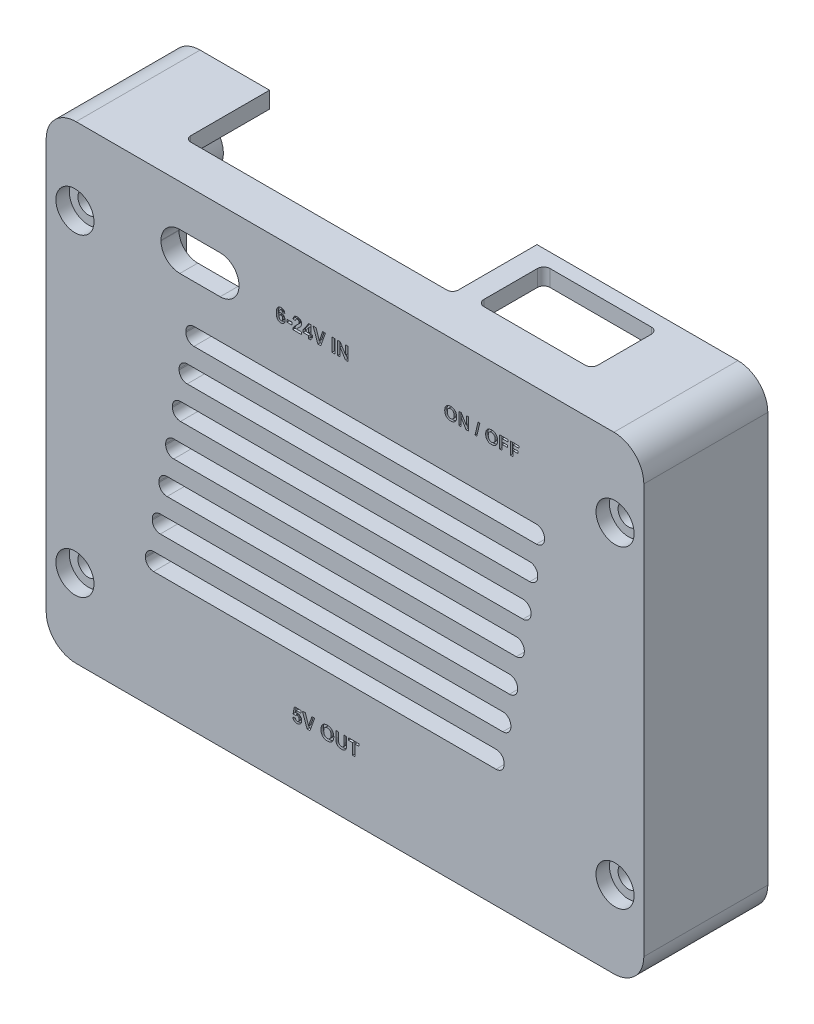
SolidWorks part; units mm, degrees
ref_plane "前视基准面" through (0, 0, 0) normal (0, 0, 1) x (1, 0, 0)
ref_plane "上视基准面" through (0, 0, 0) normal (0, 1, 0) x (1, 0, 0)
ref_plane "右视基准面" through (0, 0, 0) normal (1, 0, 0) x (0, 0, -1)
other "Configuration Table"
sketch "Lid_Envelope_80x62p8_R4" plane through (0, 0, 0) normal (0, 0, 1) x (1, 0, 0)
  line L0 (-36, -31.4) -> (36, -31.4)
  line L1 (40, -27.4) -> (40, 27.4)
  line L2 (36, 31.4) -> (-36, 31.4)
  line L3 (-40, 27.4) -> (-40, -27.4)
  arc A0 (36, -31.4) -> (40, -27.4) centre (36, -27.4) ccw
  arc A1 (40, 27.4) -> (36, 31.4) centre (36, 27.4) ccw
  arc A2 (-36, 31.4) -> (-40, 27.4) centre (-36, 27.4) ccw
  arc A3 (-40, -27.4) -> (-36, -31.4) centre (-36, -27.4) ccw
extrude "Upper_Case_Blank" add sketch "Lid_Envelope_80x62p8_R4" along normal blind 16.6 from offset 8
sketch "Upper_Case_Cavity_2p2_Wall_Profile" plane through (0, 0, 0) normal (0, 0, 1) x (1, 0, 0)
  line L0 (-36, -29.2) -> (36, -29.2)
  line L1 (37.8, -27.4) -> (37.8, 27.4)
  line L2 (36, 29.2) -> (-36, 29.2)
  line L3 (-37.8, 27.4) -> (-37.8, -27.4)
  arc A0 (36, -29.2) -> (37.8, -27.4) centre (36, -27.4) ccw
  arc A1 (37.8, 27.4) -> (36, 29.2) centre (36, 27.4) ccw
  arc A2 (-36, 29.2) -> (-37.8, 27.4) centre (-36, 27.4) ccw
  arc A3 (-37.8, -27.4) -> (-36, -29.2) centre (-36, -27.4) ccw
extrude "Upper_Case_Cavity_2p2_Wall" cut sketch "Upper_Case_Cavity_2p2_Wall_Profile" along normal blind 14.7 from offset 7.5
sketch "Upper_Lid_Screw_Guides_Profile" plane through (0, 0, 0) normal (0, 0, 1) x (1, 0, 0)
  circle A0 centre (-36.15, -21) radius 3.27
  circle A1 centre (-36.15, 21) radius 3.27
  circle A2 centre (36.15, -21) radius 3.27
  circle A3 centre (36.15, 21) radius 3.27
extrude "Upper_Lid_Screw_Guides" add sketch "Upper_Lid_Screw_Guides_Profile" along normal blind 14.3 from offset 8
sketch "Lid_M2p5_Clearance_Profiles" plane through (0, 0, 0) normal (0, 0, 1) x (1, 0, 0)
  circle A0 centre (-36.15, -21) radius 1.4
  circle A1 centre (-36.15, 21) radius 1.4
  circle A2 centre (36.15, -21) radius 1.4
  circle A3 centre (36.15, 21) radius 1.4
extrude "Four_M2p5_Lid_Clearance_Holes_D2p8" cut sketch "Lid_M2p5_Clearance_Profiles" along normal blind 17.6 from offset 7.5
sketch "Lid_Screw_Head_Recess_Profiles" plane through (0, 0, 0) normal (0, 0, 1) x (1, 0, 0)
  circle A0 centre (-36.15, -21) radius 2.55
  circle A1 centre (-36.15, 21) radius 2.55
  circle A2 centre (36.15, -21) radius 2.55
  circle A3 centre (36.15, 21) radius 2.55
extrude "Four_D5p1_Head_Counterbores" cut sketch "Lid_Screw_Head_Recess_Profiles" along normal blind 2.2 from offset 22.8
sketch "Seven_Roof_Vent_Profiles" plane through (0, 0, 0) normal (0, 0, 1) x (1, 0, 0)
  line L0 (-25.62, -15.56) -> (20.22, -15.56)
  line L1 (21.3, -14.48) -> (21.3, -14.32)
  line L2 (20.22, -13.24) -> (-25.62, -13.24)
  line L3 (-26.7, -14.32) -> (-26.7, -14.48)
  line L4 (-24.72, -10.76) -> (21.12, -10.76)
  line L5 (22.2, -9.68) -> (22.2, -9.52)
  line L6 (21.12, -8.44) -> (-24.72, -8.44)
  line L7 (-25.8, -9.52) -> (-25.8, -9.68)
  line L8 (-23.82, -5.96) -> (22.02, -5.96)
  line L9 (23.1, -4.88) -> (23.1, -4.72)
  line L10 (22.02, -3.64) -> (-23.82, -3.64)
  line L11 (-24.9, -4.72) -> (-24.9, -4.88)
  line L12 (-22.92, -1.16) -> (22.92, -1.16)
  line L13 (24, -0.08) -> (24, 0.08)
  line L14 (22.92, 1.16) -> (-22.92, 1.16)
  line L15 (-24, 0.08) -> (-24, -0.08)
  line L16 (-22.02, 3.64) -> (23.82, 3.64)
  line L17 (24.9, 4.72) -> (24.9, 4.88)
  line L18 (23.82, 5.96) -> (-22.02, 5.96)
  line L19 (-23.1, 4.88) -> (-23.1, 4.72)
  line L20 (-21.12, 8.44) -> (24.72, 8.44)
  line L21 (25.8, 9.52) -> (25.8, 9.68)
  line L22 (24.72, 10.76) -> (-21.12, 10.76)
  line L23 (-22.2, 9.68) -> (-22.2, 9.52)
  line L24 (-20.22, 13.24) -> (25.62, 13.24)
  line L25 (26.7, 14.32) -> (26.7, 14.48)
  line L26 (25.62, 15.56) -> (-20.22, 15.56)
  line L27 (-21.3, 14.48) -> (-21.3, 14.32)
  arc A0 (20.22, -15.56) -> (21.3, -14.48) centre (20.22, -14.48) ccw
  arc A1 (21.3, -14.32) -> (20.22, -13.24) centre (20.22, -14.32) ccw
  arc A2 (-25.62, -13.24) -> (-26.7, -14.32) centre (-25.62, -14.32) ccw
  arc A3 (-26.7, -14.48) -> (-25.62, -15.56) centre (-25.62, -14.48) ccw
  arc A4 (21.12, -10.76) -> (22.2, -9.68) centre (21.12, -9.68) ccw
  arc A5 (22.2, -9.52) -> (21.12, -8.44) centre (21.12, -9.52) ccw
  arc A6 (-24.72, -8.44) -> (-25.8, -9.52) centre (-24.72, -9.52) ccw
  arc A7 (-25.8, -9.68) -> (-24.72, -10.76) centre (-24.72, -9.68) ccw
  arc A8 (22.02, -5.96) -> (23.1, -4.88) centre (22.02, -4.88) ccw
  arc A9 (23.1, -4.72) -> (22.02, -3.64) centre (22.02, -4.72) ccw
  arc A10 (-23.82, -3.64) -> (-24.9, -4.72) centre (-23.82, -4.72) ccw
  arc A11 (-24.9, -4.88) -> (-23.82, -5.96) centre (-23.82, -4.88) ccw
  arc A12 (22.92, -1.16) -> (24, -0.08) centre (22.92, -0.08) ccw
  arc A13 (24, 0.08) -> (22.92, 1.16) centre (22.92, 0.08) ccw
  arc A14 (-22.92, 1.16) -> (-24, 0.08) centre (-22.92, 0.08) ccw
  arc A15 (-24, -0.08) -> (-22.92, -1.16) centre (-22.92, -0.08) ccw
  arc A16 (23.82, 3.64) -> (24.9, 4.72) centre (23.82, 4.72) ccw
  arc A17 (24.9, 4.88) -> (23.82, 5.96) centre (23.82, 4.88) ccw
  arc A18 (-22.02, 5.96) -> (-23.1, 4.88) centre (-22.02, 4.88) ccw
  arc A19 (-23.1, 4.72) -> (-22.02, 3.64) centre (-22.02, 4.72) ccw
  arc A20 (24.72, 8.44) -> (25.8, 9.52) centre (24.72, 9.52) ccw
  arc A21 (25.8, 9.68) -> (24.72, 10.76) centre (24.72, 9.68) ccw
  arc A22 (-21.12, 10.76) -> (-22.2, 9.68) centre (-21.12, 9.68) ccw
  arc A23 (-22.2, 9.52) -> (-21.12, 8.44) centre (-21.12, 9.52) ccw
  arc A24 (25.62, 13.24) -> (26.7, 14.32) centre (25.62, 14.32) ccw
  arc A25 (26.7, 14.48) -> (25.62, 15.56) centre (25.62, 14.48) ccw
  arc A26 (-20.22, 15.56) -> (-21.3, 14.48) centre (-20.22, 14.48) ccw
  arc A27 (-21.3, 14.32) -> (-20.22, 13.24) centre (-20.22, 14.32) ccw
extrude "Roof_Vent_Slots" cut sketch "Seven_Roof_Vent_Profiles" along normal blind 3.05 from offset 21.9
sketch "Terminal_Driver_Access_Profiles" plane through (0, 0, 0) normal (0, 0, 1) x (1, 0, 0)
  circle A0 centre (-21.95, 23.3) radius 2.45
  circle A1 centre (-16.87, 23.3) radius 2.45
extrude "Two_KF301_Driver_Access_D4p9" cut sketch "Terminal_Driver_Access_Profiles" along normal blind 3.05 from offset 21.9
sketch "Output_Windows_USB_C_PH_DC_Header_Profile" plane through (0, 0, 0) normal (0, 1, 0) x (1, 0, 0)
  line L0 (10.62, -15.25) -> (25.6, -15.25)
  line L1 (26.3, -14.55) -> (26.3, -6.85)
  line L2 (25.6, -6.15) -> (10.62, -6.15)
  line L3 (9.92, -6.85) -> (9.92, -14.55)
  line L4 (-28.53, -5.65) -> (7.8, -5.65)
  line L5 (7.8, -5.65) -> (8.45, -6.3)
  line L6 (8.45, -6.3) -> (8.45, -17.9)
  line L7 (8.45, -17.9) -> (7.8, -18.55)
  line L8 (7.8, -18.55) -> (-3.4, -18.55)
  line L9 (-3.4, -18.55) -> (-4.05, -17.9)
  line L10 (-4.05, -17.9) -> (-4.05, -14.03)
  line L11 (-4.05, -14.03) -> (-4.7, -13.38)
  line L12 (-4.7, -13.38) -> (-28.53, -13.38)
  line L13 (-28.53, -13.38) -> (-29.18, -12.73)
  line L14 (-29.18, -12.73) -> (-29.18, -6.3)
  line L15 (-29.18, -6.3) -> (-28.53, -5.65)
  arc A0 (25.6, -15.25) -> (26.3, -14.55) centre (25.6, -14.55) ccw
  arc A1 (26.3, -6.85) -> (25.6, -6.15) centre (25.6, -6.85) ccw
  arc A2 (10.62, -6.15) -> (9.92, -6.85) centre (10.62, -6.85) ccw
  arc A3 (9.92, -14.55) -> (10.62, -15.25) centre (10.62, -14.55) ccw
extrude "Output_Windows_USB_C_PH_DC_Header" cut sketch "Output_Windows_USB_C_PH_DC_Header_Profile" along normal blind 3.9 from offset 32.4
sketch "Input_Windows_KF301_XH_DC_Switch_Profile" plane through (0, 0, 0) normal (0, 1, 0) x (1, 0, 0)
  line L0 (-25.95, -19.3) -> (8.35, -19.3)
  line L1 (9.1, -18.55) -> (9.1, -6.9)
  line L2 (8.35, -6.15) -> (-25.95, -6.15)
  line L3 (-26.7, -6.9) -> (-26.7, -18.55)
  line L4 (12.75, -18.75) -> (26.3, -18.75)
  line L5 (27.15, -17.9) -> (27.15, -10.75)
  line L6 (26.3, -9.9) -> (12.75, -9.9)
  line L7 (11.9, -10.75) -> (11.9, -17.9)
  arc A0 (8.35, -19.3) -> (9.1, -18.55) centre (8.35, -18.55) ccw
  arc A1 (9.1, -6.9) -> (8.35, -6.15) centre (8.35, -6.9) ccw
  arc A2 (-25.95, -6.15) -> (-26.7, -6.9) centre (-25.95, -6.9) ccw
  arc A3 (-26.7, -18.55) -> (-25.95, -19.3) centre (-25.95, -18.55) ccw
  arc A4 (26.3, -18.75) -> (27.15, -17.9) centre (26.3, -17.9) ccw
  arc A5 (27.15, -10.75) -> (26.3, -9.9) centre (26.3, -10.75) ccw
  arc A6 (12.75, -9.9) -> (11.9, -10.75) centre (12.75, -10.75) ccw
  arc A7 (11.9, -17.9) -> (12.75, -18.75) centre (12.75, -17.9) ccw
extrude "Input_Windows_KF301_XH_DC_Switch" cut sketch "Input_Windows_KF301_XH_DC_Switch_Profile" against normal blind 3.9 from offset 32.4
sketch "Input_Label_Letter_Profiles" plane through (0, 0, 0) normal (0, 0, 1) x (1, 0, 0)
  line L0 (-8.0456, 23.1366) -> (-8.374, 23.1003)
  line L1 (-8.374, 23.1003) -> (-8.3957, 23.1885)
  line L2 (-8.3957, 23.1885) -> (-8.4367, 23.2501)
  line L3 (-8.4367, 23.2501) -> (-8.495, 23.2863)
  line L4 (-8.495, 23.2863) -> (-8.5683, 23.2983)
  line L5 (-8.5683, 23.2983) -> (-8.6675, 23.2742)
  line L6 (-8.6675, 23.2742) -> (-8.75, 23.2018)
  line L7 (-8.75, 23.2018) -> (-8.7837, 23.1404)
  line L8 (-8.7837, 23.1404) -> (-8.8106, 23.0529)
  line L9 (-8.8106, 23.0529) -> (-8.8305, 22.9394)
  line L10 (-8.8305, 22.9394) -> (-8.8436, 22.7997)
  line L11 (-8.8436, 22.7997) -> (-8.7523, 22.8829)
  line L12 (-8.7523, 22.8829) -> (-8.6472, 22.9328)
  line L13 (-8.6472, 22.9328) -> (-8.5285, 22.9494)
  line L14 (-8.5285, 22.9494) -> (-8.4261, 22.9393)
  line L15 (-8.4261, 22.9393) -> (-8.3312, 22.909)
  line L16 (-8.3312, 22.909) -> (-8.244, 22.8584)
  line L17 (-8.244, 22.8584) -> (-8.1645, 22.7876)
  line L18 (-8.1645, 22.7876) -> (-8.0982, 22.7008)
  line L19 (-8.0982, 22.7008) -> (-8.0508, 22.6023)
  line L20 (-8.0508, 22.6023) -> (-8.0224, 22.492)
  line L21 (-8.0224, 22.492) -> (-8.013, 22.3699)
  line L22 (-8.013, 22.3699) -> (-8.0193, 22.2655)
  line L23 (-8.0193, 22.2655) -> (-8.0384, 22.1697)
  line L24 (-8.0384, 22.1697) -> (-8.0703, 22.0826)
  line L25 (-8.0703, 22.0826) -> (-8.115, 22.004)
  line L26 (-8.115, 22.004) -> (-8.1723, 21.934)
  line L27 (-8.1723, 21.934) -> (-8.2577, 21.8622)
  line L28 (-8.2577, 21.8622) -> (-8.3543, 21.8109)
  line L29 (-8.3543, 21.8109) -> (-8.4623, 21.7801)
  line L30 (-8.4623, 21.7801) -> (-8.5816, 21.7698)
  line L31 (-8.5816, 21.7698) -> (-8.685, 21.7782)
  line L32 (-8.685, 21.7782) -> (-8.7808, 21.8031)
  line L33 (-8.7808, 21.8031) -> (-8.8689, 21.8448)
  line L34 (-8.8689, 21.8448) -> (-8.9494, 21.9031)
  line L35 (-8.9494, 21.9031) -> (-9.0223, 21.9781)
  line L36 (-9.0223, 21.9781) -> (-9.0845, 22.072)
  line L37 (-9.0845, 22.072) -> (-9.1328, 22.1873)
  line L38 (-9.1328, 22.1873) -> (-9.1673, 22.3239)
  line L39 (-9.1673, 22.3239) -> (-9.1881, 22.4817)
  line L40 (-9.1881, 22.4817) -> (-9.195, 22.6608)
  line L41 (-9.195, 22.6608) -> (-9.1878, 22.8446)
  line L42 (-9.1878, 22.8446) -> (-9.1662, 23.0066)
  line L43 (-9.1662, 23.0066) -> (-9.1302, 23.1469)
  line L44 (-9.1302, 23.1469) -> (-9.0798, 23.2655)
  line L45 (-9.0798, 23.2655) -> (-9.0151, 23.3623)
  line L46 (-9.0151, 23.3623) -> (-8.9388, 23.4397)
  line L47 (-8.9388, 23.4397) -> (-8.8539, 23.4999)
  line L48 (-8.8539, 23.4999) -> (-8.7605, 23.5429)
  line L49 (-8.7605, 23.5429) -> (-8.6585, 23.5687)
  line L50 (-8.6585, 23.5687) -> (-8.5478, 23.5772)
  line L51 (-8.5478, 23.5772) -> (-8.4211, 23.5647)
  line L52 (-8.4211, 23.5647) -> (-8.3098, 23.5271)
  line L53 (-8.3098, 23.5271) -> (-8.214, 23.4644)
  line L54 (-8.214, 23.4644) -> (-8.1539, 23.4015)
  line L55 (-8.1539, 23.4015) -> (-8.1058, 23.326)
  line L56 (-8.1058, 23.326) -> (-8.0697, 23.2376)
  line L57 (-8.0697, 23.2376) -> (-8.0456, 23.1366)
  line L58 (-8.8146, 22.3964) -> (-8.8062, 22.2946)
  line L59 (-8.8062, 22.2946) -> (-8.7808, 22.2094)
  line L60 (-8.7808, 22.2094) -> (-8.7386, 22.1411)
  line L61 (-8.7386, 22.1411) -> (-8.6571, 22.0736)
  line L62 (-8.6571, 22.0736) -> (-8.5647, 22.0511)
  line L63 (-8.5647, 22.0511) -> (-8.4784, 22.0695)
  line L64 (-8.4784, 22.0695) -> (-8.4078, 22.1248)
  line L65 (-8.4078, 22.1248) -> (-8.3607, 22.222)
  line L66 (-8.3607, 22.222) -> (-8.345, 22.3663)
  line L67 (-8.345, 22.3663) -> (-8.3525, 22.4711)
  line L68 (-8.3525, 22.4711) -> (-8.375, 22.5554)
  line L69 (-8.375, 22.5554) -> (-8.4126, 22.6192)
  line L70 (-8.4126, 22.6192) -> (-8.4886, 22.6794)
  line L71 (-8.4886, 22.6794) -> (-8.5816, 22.6995)
  line L72 (-8.5816, 22.6995) -> (-8.6719, 22.6803)
  line L73 (-8.6719, 22.6803) -> (-8.747, 22.6228)
  line L74 (-8.747, 22.6228) -> (-8.7977, 22.5279)
  line L75 (-8.7977, 22.5279) -> (-8.8146, 22.3964)
  line L76 (-7.7642, 22.2721) -> (-7.7642, 22.6114)
  line L77 (-7.7642, 22.6114) -> (-7.0978, 22.6114)
  line L78 (-7.0978, 22.6114) -> (-7.0978, 22.2721)
  line L79 (-7.0978, 22.2721) -> (-7.7642, 22.2721)
  line L80 (-5.8071, 22.1151) -> (-5.8071, 21.8)
  line L81 (-5.8071, 21.8) -> (-6.9963, 21.8)
  line L82 (-6.9963, 21.8) -> (-6.9749, 21.917)
  line L83 (-6.9749, 21.917) -> (-6.9362, 22.0299)
  line L84 (-6.9362, 22.0299) -> (-6.8804, 22.1387)
  line L85 (-6.8804, 22.1387) -> (-6.8343, 22.2068)
  line L86 (-6.8343, 22.2068) -> (-6.773, 22.2834)
  line L87 (-6.773, 22.2834) -> (-6.6967, 22.3682)
  line L88 (-6.6967, 22.3682) -> (-6.6053, 22.4615)
  line L89 (-6.6053, 22.4615) -> (-6.4989, 22.5631)
  line L90 (-6.4989, 22.5631) -> (-6.3953, 22.6613)
  line L91 (-6.3953, 22.6613) -> (-6.3139, 22.7423)
  line L92 (-6.3139, 22.7423) -> (-6.2546, 22.8062)
  line L93 (-6.2546, 22.8062) -> (-6.2176, 22.8528)
  line L94 (-6.2176, 22.8528) -> (-6.1651, 22.9573)
  line L95 (-6.1651, 22.9573) -> (-6.1476, 23.0605)
  line L96 (-6.1476, 23.0605) -> (-6.1628, 23.1608)
  line L97 (-6.1628, 23.1608) -> (-6.2085, 23.235)
  line L98 (-6.2085, 23.235) -> (-6.2811, 23.2807)
  line L99 (-6.2811, 23.2807) -> (-6.377, 23.2959)
  line L100 (-6.377, 23.2959) -> (-6.4723, 23.2799)
  line L101 (-6.4723, 23.2799) -> (-6.546, 23.2319)
  line L102 (-6.546, 23.2319) -> (-6.5955, 23.1468)
  line L103 (-6.5955, 23.1468) -> (-6.6184, 23.0194)
  line L104 (-6.6184, 23.0194) -> (-6.9565, 23.0532)
  line L105 (-6.9565, 23.0532) -> (-6.9333, 23.1834)
  line L106 (-6.9333, 23.1834) -> (-6.894, 23.2938)
  line L107 (-6.894, 23.2938) -> (-6.8386, 23.3844)
  line L108 (-6.8386, 23.3844) -> (-6.7669, 23.4553)
  line L109 (-6.7669, 23.4553) -> (-6.6823, 23.5086)
  line L110 (-6.6823, 23.5086) -> (-6.5877, 23.5468)
  line L111 (-6.5877, 23.5468) -> (-6.4831, 23.5696)
  line L112 (-6.4831, 23.5696) -> (-6.3685, 23.5772)
  line L113 (-6.3685, 23.5772) -> (-6.2445, 23.5684)
  line L114 (-6.2445, 23.5684) -> (-6.1346, 23.5419)
  line L115 (-6.1346, 23.5419) -> (-6.0387, 23.4978)
  line L116 (-6.0387, 23.4978) -> (-5.9568, 23.436)
  line L117 (-5.9568, 23.436) -> (-5.8913, 23.361)
  line L118 (-5.8913, 23.361) -> (-5.8445, 23.2775)
  line L119 (-5.8445, 23.2775) -> (-5.8164, 23.1854)
  line L120 (-5.8164, 23.1854) -> (-5.8071, 23.0846)
  line L121 (-5.8071, 23.0846) -> (-5.8178, 22.968)
  line L122 (-5.8178, 22.968) -> (-5.8499, 22.8571)
  line L123 (-5.8499, 22.8571) -> (-5.9053, 22.7464)
  line L124 (-5.9053, 22.7464) -> (-5.9858, 22.6307)
  line L125 (-5.9858, 22.6307) -> (-6.0378, 22.5707)
  line L126 (-6.0378, 22.5707) -> (-6.1119, 22.4954)
  line L127 (-6.1119, 22.4954) -> (-6.2079, 22.4049)
  line L128 (-6.2079, 22.4049) -> (-6.3019, 22.3177)
  line L129 (-6.3019, 22.3177) -> (-6.3697, 22.2525)
  line L130 (-6.3697, 22.2525) -> (-6.4114, 22.2093)
  line L131 (-6.4114, 22.2093) -> (-6.4502, 22.1616)
  line L132 (-6.4502, 22.1616) -> (-6.4808, 22.1151)
  line L133 (-6.4808, 22.1151) -> (-5.8071, 22.1151)
  line L134 (-4.8907, 21.8) -> (-4.8907, 22.1562)
  line L135 (-4.8907, 22.1562) -> (-5.6151, 22.1562)
  line L136 (-5.6151, 22.1562) -> (-5.6151, 22.4532)
  line L137 (-5.6151, 22.4532) -> (-4.8472, 23.5772)
  line L138 (-4.8472, 23.5772) -> (-4.5623, 23.5772)
  line L139 (-4.5623, 23.5772) -> (-4.5623, 22.4544)
  line L140 (-4.5623, 22.4544) -> (-4.3426, 22.4544)
  line L141 (-4.3426, 22.4544) -> (-4.3426, 22.1562)
  line L142 (-4.3426, 22.1562) -> (-4.5623, 22.1562)
  line L143 (-4.5623, 22.1562) -> (-4.5623, 21.8)
  line L144 (-4.5623, 21.8) -> (-4.8907, 21.8)
  line L145 (-4.8907, 22.4544) -> (-4.8907, 23.0593)
  line L146 (-4.8907, 23.0593) -> (-5.2976, 22.4544)
  line L147 (-5.2976, 22.4544) -> (-4.8907, 22.4544)
  line L148 (-3.6326, 21.8) -> (-4.2653, 23.57)
  line L149 (-4.2653, 23.57) -> (-3.8777, 23.57)
  line L150 (-3.8777, 23.57) -> (-3.4298, 22.26)
  line L151 (-3.4298, 22.26) -> (-2.9963, 23.57)
  line L152 (-2.9963, 23.57) -> (-2.6172, 23.57)
  line L153 (-2.6172, 23.57) -> (-3.2511, 21.8)
  line L154 (-3.2511, 21.8) -> (-3.6326, 21.8)
  line L155 (-1.7153, 21.8) -> (-1.7153, 23.57)
  line L156 (-1.7153, 23.57) -> (-1.3579, 23.57)
  line L157 (-1.3579, 23.57) -> (-1.3579, 21.8)
  line L158 (-1.3579, 21.8) -> (-1.7153, 21.8)
  line L159 (-0.9921, 21.8) -> (-0.9921, 23.57)
  line L160 (-0.9921, 23.57) -> (-0.6444, 23.57)
  line L161 (-0.6444, 23.57) -> (0.08, 22.388)
  line L162 (0.08, 22.388) -> (0.08, 23.57)
  line L163 (0.08, 23.57) -> (0.4121, 23.57)
  line L164 (0.4121, 23.57) -> (0.4121, 21.8)
  line L165 (0.4121, 21.8) -> (0.0535, 21.8)
  line L166 (0.0535, 21.8) -> (-0.6601, 22.9542)
  line L167 (-0.6601, 22.9542) -> (-0.6601, 21.8)
  line L168 (-0.6601, 21.8) -> (-0.9921, 21.8)
extrude "Input_Label" cut sketch "Input_Label_Letter_Profiles" along normal blind 0.5 from offset 24.29
sketch "Output_Label_Letter_Profiles" plane through (0, 0, 0) normal (0, 0, 1) x (1, 0, 0)
  line L0 (-6.9901, -23.0948) -> (-6.6521, -23.0598)
  line L1 (-6.6521, -23.0598) -> (-6.6234, -23.1626)
  line L2 (-6.6234, -23.1626) -> (-6.5663, -23.2415)
  line L3 (-6.5663, -23.2415) -> (-6.4897, -23.2918)
  line L4 (-6.4897, -23.2918) -> (-6.4021, -23.3085)
  line L5 (-6.4021, -23.3085) -> (-6.304, -23.2869)
  line L6 (-6.304, -23.2869) -> (-6.2222, -23.2222)
  line L7 (-6.2222, -23.2222) -> (-6.1813, -23.1549)
  line L8 (-6.1813, -23.1549) -> (-6.1568, -23.0682)
  line L9 (-6.1568, -23.0682) -> (-6.1486, -22.962)
  line L10 (-6.1486, -22.962) -> (-6.1669, -22.8194)
  line L11 (-6.1669, -22.8194) -> (-6.2216, -22.7175)
  line L12 (-6.2216, -22.7175) -> (-6.3057, -22.6564)
  line L13 (-6.3057, -22.6564) -> (-6.4118, -22.636)
  line L14 (-6.4118, -22.636) -> (-6.5058, -22.6504)
  line L15 (-6.5058, -22.6504) -> (-6.5932, -22.6934)
  line L16 (-6.5932, -22.6934) -> (-6.6738, -22.7652)
  line L17 (-6.6738, -22.7652) -> (-6.9491, -22.7254)
  line L18 (-6.9491, -22.7254) -> (-6.7752, -21.8041)
  line L19 (-6.7752, -21.8041) -> (-5.8781, -21.8041)
  line L20 (-5.8781, -21.8041) -> (-5.8781, -22.1217)
  line L21 (-5.8781, -22.1217) -> (-6.518, -22.1217)
  line L22 (-6.518, -22.1217) -> (-6.5712, -22.4223)
  line L23 (-6.5712, -22.4223) -> (-6.4565, -22.3798)
  line L24 (-6.4565, -22.3798) -> (-6.3394, -22.3656)
  line L25 (-6.3394, -22.3656) -> (-6.2308, -22.3758)
  line L26 (-6.2308, -22.3758) -> (-6.1308, -22.4066)
  line L27 (-6.1308, -22.4066) -> (-6.0394, -22.4579)
  line L28 (-6.0394, -22.4579) -> (-5.9566, -22.5298)
  line L29 (-5.9566, -22.5298) -> (-5.888, -22.618)
  line L30 (-5.888, -22.618) -> (-5.8389, -22.7184)
  line L31 (-5.8389, -22.7184) -> (-5.8095, -22.8311)
  line L32 (-5.8095, -22.8311) -> (-5.7997, -22.956)
  line L33 (-5.7997, -22.956) -> (-5.8076, -23.0623)
  line L34 (-5.8076, -23.0623) -> (-5.8314, -23.1627)
  line L35 (-5.8314, -23.1627) -> (-5.871, -23.2573)
  line L36 (-5.871, -23.2573) -> (-5.9264, -23.3459)
  line L37 (-5.9264, -23.3459) -> (-6.0009, -23.4303)
  line L38 (-6.0009, -23.4303) -> (-6.086, -23.4959)
  line L39 (-6.086, -23.4959) -> (-6.1819, -23.5427)
  line L40 (-6.1819, -23.5427) -> (-6.2885, -23.5708)
  line L41 (-6.2885, -23.5708) -> (-6.4058, -23.5802)
  line L42 (-6.4058, -23.5802) -> (-6.5226, -23.572)
  line L43 (-6.5226, -23.572) -> (-6.6282, -23.5473)
  line L44 (-6.6282, -23.5473) -> (-6.7225, -23.5062)
  line L45 (-6.7225, -23.5062) -> (-6.8054, -23.4486)
  line L46 (-6.8054, -23.4486) -> (-6.8749, -23.3771)
  line L47 (-6.8749, -23.3771) -> (-6.9289, -23.2943)
  line L48 (-6.9289, -23.2943) -> (-6.9673, -23.2002)
  line L49 (-6.9673, -23.2002) -> (-6.9901, -23.0948)
  line L50 (-5.0716, -23.55) -> (-5.7043, -21.78)
  line L51 (-5.7043, -21.78) -> (-5.3167, -21.78)
  line L52 (-5.3167, -21.78) -> (-4.8688, -23.09)
  line L53 (-4.8688, -23.09) -> (-4.4353, -21.78)
  line L54 (-4.4353, -21.78) -> (-4.0562, -21.78)
  line L55 (-4.0562, -21.78) -> (-4.6901, -23.55)
  line L56 (-4.6901, -23.55) -> (-5.0716, -23.55)
  line L57 (-3.2159, -22.6759) -> (-3.2108, -22.5461)
  line L58 (-3.2108, -22.5461) -> (-3.1957, -22.4272)
  line L59 (-3.1957, -22.4272) -> (-3.1704, -22.3191)
  line L60 (-3.1704, -22.3191) -> (-3.135, -22.2219)
  line L61 (-3.135, -22.2219) -> (-3.0899, -22.1348)
  line L62 (-3.0899, -22.1348) -> (-3.0349, -22.0539)
  line L63 (-3.0349, -22.0539) -> (-2.9702, -21.9792)
  line L64 (-2.9702, -21.9792) -> (-2.8984, -21.9138)
  line L65 (-2.8984, -21.9138) -> (-2.8221, -21.8606)
  line L66 (-2.8221, -21.8606) -> (-2.7414, -21.8198)
  line L67 (-2.7414, -21.8198) -> (-2.6555, -21.7892)
  line L68 (-2.6555, -21.7892) -> (-2.5633, -21.7673)
  line L69 (-2.5633, -21.7673) -> (-2.4648, -21.7542)
  line L70 (-2.4648, -21.7542) -> (-2.3599, -21.7498)
  line L71 (-2.3599, -21.7498) -> (-2.2097, -21.7595)
  line L72 (-2.2097, -21.7595) -> (-2.0719, -21.7886)
  line L73 (-2.0719, -21.7886) -> (-1.9467, -21.8372)
  line L74 (-1.9467, -21.8372) -> (-1.834, -21.9051)
  line L75 (-1.834, -21.9051) -> (-1.7339, -21.9925)
  line L76 (-1.7339, -21.9925) -> (-1.6493, -22.0971)
  line L77 (-1.6493, -22.0971) -> (-1.5836, -22.217)
  line L78 (-1.5836, -22.217) -> (-1.5366, -22.3519)
  line L79 (-1.5366, -22.3519) -> (-1.5084, -22.5021)
  line L80 (-1.5084, -22.5021) -> (-1.499, -22.6674)
  line L81 (-1.499, -22.6674) -> (-1.5084, -22.8314)
  line L82 (-1.5084, -22.8314) -> (-1.5363, -22.9805)
  line L83 (-1.5363, -22.9805) -> (-1.5829, -23.1146)
  line L84 (-1.5829, -23.1146) -> (-1.6482, -23.2338)
  line L85 (-1.6482, -23.2338) -> (-1.7321, -23.3381)
  line L86 (-1.7321, -23.3381) -> (-1.8315, -23.4252)
  line L87 (-1.8315, -23.4252) -> (-1.9436, -23.493)
  line L88 (-1.9436, -23.493) -> (-2.0682, -23.5415)
  line L89 (-2.0682, -23.5415) -> (-2.2053, -23.5705)
  line L90 (-2.2053, -23.5705) -> (-2.355, -23.5802)
  line L91 (-2.355, -23.5802) -> (-2.5065, -23.5706)
  line L92 (-2.5065, -23.5706) -> (-2.645, -23.5417)
  line L93 (-2.645, -23.5417) -> (-2.7706, -23.4935)
  line L94 (-2.7706, -23.4935) -> (-2.8832, -23.426)
  line L95 (-2.8832, -23.426) -> (-2.9829, -23.3393)
  line L96 (-2.9829, -23.3393) -> (-3.0668, -23.2357)
  line L97 (-3.0668, -23.2357) -> (-3.132, -23.1176)
  line L98 (-3.132, -23.1176) -> (-3.1786, -22.9849)
  line L99 (-3.1786, -22.9849) -> (-3.2066, -22.8376)
  line L100 (-3.2066, -22.8376) -> (-3.2159, -22.6759)
  line L101 (-2.8476, -22.6638) -> (-2.8421, -22.7782)
  line L102 (-2.8421, -22.7782) -> (-2.8254, -22.881)
  line L103 (-2.8254, -22.881) -> (-2.7977, -22.9722)
  line L104 (-2.7977, -22.9722) -> (-2.7588, -23.0517)
  line L105 (-2.7588, -23.0517) -> (-2.7088, -23.1196)
  line L106 (-2.7088, -23.1196) -> (-2.6347, -23.1874)
  line L107 (-2.6347, -23.1874) -> (-2.5512, -23.2359)
  line L108 (-2.5512, -23.2359) -> (-2.4584, -23.265)
  line L109 (-2.4584, -23.265) -> (-2.3563, -23.2747)
  line L110 (-2.3563, -23.2747) -> (-2.2542, -23.2651)
  line L111 (-2.2542, -23.2651) -> (-2.1617, -23.2362)
  line L112 (-2.1617, -23.2362) -> (-2.0788, -23.1881)
  line L113 (-2.0788, -23.1881) -> (-2.0055, -23.1208)
  line L114 (-2.0055, -23.1208) -> (-1.9562, -23.053)
  line L115 (-1.9562, -23.053) -> (-1.9178, -22.973)
  line L116 (-1.9178, -22.973) -> (-1.8904, -22.8806)
  line L117 (-1.8904, -22.8806) -> (-1.874, -22.776)
  line L118 (-1.874, -22.776) -> (-1.8685, -22.659)
  line L119 (-1.8685, -22.659) -> (-1.8738, -22.5434)
  line L120 (-1.8738, -22.5434) -> (-1.8898, -22.4403)
  line L121 (-1.8898, -22.4403) -> (-1.9165, -22.3495)
  line L122 (-1.9165, -22.3495) -> (-1.9539, -22.2711)
  line L123 (-1.9539, -22.2711) -> (-2.0019, -22.205)
  line L124 (-2.0019, -22.205) -> (-2.0741, -22.1395)
  line L125 (-2.0741, -22.1395) -> (-2.1572, -22.0927)
  line L126 (-2.1572, -22.0927) -> (-2.2513, -22.0646)
  line L127 (-2.2513, -22.0646) -> (-2.3563, -22.0553)
  line L128 (-2.3563, -22.0553) -> (-2.4614, -22.0648)
  line L129 (-2.4614, -22.0648) -> (-2.5558, -22.0932)
  line L130 (-2.5558, -22.0932) -> (-2.6395, -22.1405)
  line L131 (-2.6395, -22.1405) -> (-2.7124, -22.2068)
  line L132 (-2.7124, -22.2068) -> (-2.7611, -22.2736)
  line L133 (-2.7611, -22.2736) -> (-2.799, -22.3527)
  line L134 (-2.799, -22.3527) -> (-2.826, -22.4441)
  line L135 (-2.826, -22.4441) -> (-2.8422, -22.5478)
  line L136 (-2.8422, -22.5478) -> (-2.8476, -22.6638)
  line L137 (-1.2008, -21.78) -> (-0.8434, -21.78)
  line L138 (-0.8434, -21.78) -> (-0.8434, -22.7386)
  line L139 (-0.8434, -22.7386) -> (-0.8419, -22.8729)
  line L140 (-0.8419, -22.8729) -> (-0.8375, -22.9715)
  line L141 (-0.8375, -22.9715) -> (-0.8301, -23.0344)
  line L142 (-0.8301, -23.0344) -> (-0.7914, -23.1324)
  line L143 (-0.7914, -23.1324) -> (-0.7209, -23.2089)
  line L144 (-0.7209, -23.2089) -> (-0.6187, -23.2583)
  line L145 (-0.6187, -23.2583) -> (-0.4848, -23.2747)
  line L146 (-0.4848, -23.2747) -> (-0.3514, -23.2592)
  line L147 (-0.3514, -23.2592) -> (-0.2554, -23.2125)
  line L148 (-0.2554, -23.2125) -> (-0.1936, -23.1433)
  line L149 (-0.1936, -23.1433) -> (-0.1625, -23.0598)
  line L150 (-0.1625, -23.0598) -> (-0.1537, -22.9862)
  line L151 (-0.1537, -22.9862) -> (-0.1485, -22.886)
  line L152 (-0.1485, -22.886) -> (-0.1468, -22.7592)
  line L153 (-0.1468, -22.7592) -> (-0.1468, -21.78)
  line L154 (-0.1468, -21.78) -> (0.2106, -21.78)
  line L155 (0.2106, -21.78) -> (0.2106, -22.7097)
  line L156 (0.2106, -22.7097) -> (0.2088, -22.8574)
  line L157 (0.2088, -22.8574) -> (0.2034, -22.9816)
  line L158 (0.2034, -22.9816) -> (0.1943, -23.0825)
  line L159 (0.1943, -23.0825) -> (0.1816, -23.16)
  line L160 (0.1816, -23.16) -> (0.1404, -23.2814)
  line L161 (0.1404, -23.2814) -> (0.0748, -23.3822)
  line L162 (0.0748, -23.3822) -> (-0.0162, -23.4635)
  line L163 (-0.0162, -23.4635) -> (-0.1335, -23.5265)
  line L164 (-0.1335, -23.5265) -> (-0.2293, -23.5563)
  line L165 (-0.2293, -23.5563) -> (-0.3428, -23.5742)
  line L166 (-0.3428, -23.5742) -> (-0.474, -23.5802)
  line L167 (-0.474, -23.5802) -> (-0.5931, -23.5765)
  line L168 (-0.5931, -23.5765) -> (-0.6969, -23.5655)
  line L169 (-0.6969, -23.5655) -> (-0.7854, -23.5472)
  line L170 (-0.7854, -23.5472) -> (-0.8585, -23.5216)
  line L171 (-0.8585, -23.5216) -> (-0.9758, -23.4543)
  line L172 (-0.9758, -23.4543) -> (-1.0656, -23.3695)
  line L173 (-1.0656, -23.3695) -> (-1.1287, -23.2737)
  line L174 (-1.1287, -23.2737) -> (-1.1658, -23.1733)
  line L175 (-1.1658, -23.1733) -> (-1.1811, -23.0882)
  line L176 (-1.1811, -23.0882) -> (-1.1921, -22.985)
  line L177 (-1.1921, -22.985) -> (-1.1986, -22.8636)
  line L178 (-1.1986, -22.8636) -> (-1.2008, -22.7242)
  line L179 (-1.2008, -22.7242) -> (-1.2008, -21.78)
  line L180 (1.0075, -23.55) -> (1.0075, -22.0794)
  line L181 (1.0075, -22.0794) -> (0.4823, -22.0794)
  line L182 (0.4823, -22.0794) -> (0.4823, -21.78)
  line L183 (0.4823, -21.78) -> (1.8888, -21.78)
  line L184 (1.8888, -21.78) -> (1.8888, -22.0794)
  line L185 (1.8888, -22.0794) -> (1.3648, -22.0794)
  line L186 (1.3648, -22.0794) -> (1.3648, -23.55)
  line L187 (1.3648, -23.55) -> (1.0075, -23.55)
extrude "Output_Label" cut sketch "Output_Label_Letter_Profiles" along normal blind 0.5 from offset 24.29
sketch "Switch_Label_Letter_Profiles" plane through (0, 0, 0) normal (0, 0, 1) x (1, 0, 0)
  line L0 (13.3502, 22.6149) -> (13.3549, 22.7359)
  line L1 (13.3549, 22.7359) -> (13.369, 22.8467)
  line L2 (13.369, 22.8467) -> (13.3926, 22.9475)
  line L3 (13.3926, 22.9475) -> (13.4256, 23.0381)
  line L4 (13.4256, 23.0381) -> (13.4677, 23.1192)
  line L5 (13.4677, 23.1192) -> (13.5189, 23.1946)
  line L6 (13.5189, 23.1946) -> (13.5792, 23.2643)
  line L7 (13.5792, 23.2643) -> (13.6812, 23.3515)
  line L8 (13.6812, 23.3515) -> (13.7925, 23.4129)
  line L9 (13.7925, 23.4129) -> (13.9006, 23.4491)
  line L10 (13.9006, 23.4491) -> (14.0191, 23.4709)
  line L11 (14.0191, 23.4709) -> (14.1482, 23.4781)
  line L12 (14.1482, 23.4781) -> (14.2882, 23.4691)
  line L13 (14.2882, 23.4691) -> (14.4166, 23.4419)
  line L14 (14.4166, 23.4419) -> (14.5333, 23.3967)
  line L15 (14.5333, 23.3967) -> (14.6383, 23.3333)
  line L16 (14.6383, 23.3333) -> (14.7317, 23.2519)
  line L17 (14.7317, 23.2519) -> (14.8105, 23.1544)
  line L18 (14.8105, 23.1544) -> (14.8718, 23.0426)
  line L19 (14.8718, 23.0426) -> (14.9156, 22.9168)
  line L20 (14.9156, 22.9168) -> (14.9419, 22.7768)
  line L21 (14.9419, 22.7768) -> (14.9506, 22.6227)
  line L22 (14.9506, 22.6227) -> (14.942, 22.4699)
  line L23 (14.942, 22.4699) -> (14.9159, 22.3309)
  line L24 (14.9159, 22.3309) -> (14.8725, 22.2059)
  line L25 (14.8725, 22.2059) -> (14.8116, 22.0948)
  line L26 (14.8116, 22.0948) -> (14.7334, 21.9975)
  line L27 (14.7334, 21.9975) -> (14.6407, 21.9163)
  line L28 (14.6407, 21.9163) -> (14.5362, 21.8531)
  line L29 (14.5362, 21.8531) -> (14.4201, 21.808)
  line L30 (14.4201, 21.808) -> (14.2922, 21.7809)
  line L31 (14.2922, 21.7809) -> (14.1527, 21.7719)
  line L32 (14.1527, 21.7719) -> (14.0115, 21.7808)
  line L33 (14.0115, 21.7808) -> (13.8824, 21.8078)
  line L34 (13.8824, 21.8078) -> (13.7653, 21.8527)
  line L35 (13.7653, 21.8527) -> (13.6603, 21.9156)
  line L36 (13.6603, 21.9156) -> (13.5674, 21.9964)
  line L37 (13.5674, 21.9964) -> (13.4892, 22.093)
  line L38 (13.4892, 22.093) -> (13.4284, 22.2031)
  line L39 (13.4284, 22.2031) -> (13.3849, 22.3268)
  line L40 (13.3849, 22.3268) -> (13.3589, 22.4641)
  line L41 (13.3589, 22.4641) -> (13.3502, 22.6149)
  line L42 (13.6935, 22.6261) -> (13.7015, 22.4945)
  line L43 (13.7015, 22.4945) -> (13.7258, 22.3798)
  line L44 (13.7258, 22.3798) -> (13.7663, 22.282)
  line L45 (13.7663, 22.282) -> (13.8229, 22.2012)
  line L46 (13.8229, 22.2012) -> (13.892, 22.138)
  line L47 (13.892, 22.138) -> (13.9698, 22.0928)
  line L48 (13.9698, 22.0928) -> (14.0563, 22.0657)
  line L49 (14.0563, 22.0657) -> (14.1515, 22.0566)
  line L50 (14.1515, 22.0566) -> (14.2467, 22.0656)
  line L51 (14.2467, 22.0656) -> (14.3329, 22.0925)
  line L52 (14.3329, 22.0925) -> (14.4102, 22.1373)
  line L53 (14.4102, 22.1373) -> (14.4785, 22.2001)
  line L54 (14.4785, 22.2001) -> (14.5344, 22.2808)
  line L55 (14.5344, 22.2808) -> (14.5743, 22.3795)
  line L56 (14.5743, 22.3795) -> (14.5983, 22.4961)
  line L57 (14.5983, 22.4961) -> (14.6062, 22.6306)
  line L58 (14.6062, 22.6306) -> (14.5985, 22.7634)
  line L59 (14.5985, 22.7634) -> (14.5752, 22.8782)
  line L60 (14.5752, 22.8782) -> (14.5363, 22.975)
  line L61 (14.5363, 22.975) -> (14.4819, 23.0538)
  line L62 (14.4819, 23.0538) -> (14.4146, 23.1149)
  line L63 (14.4146, 23.1149) -> (14.3371, 23.1585)
  line L64 (14.3371, 23.1585) -> (14.2494, 23.1847)
  line L65 (14.2494, 23.1847) -> (14.1515, 23.1934)
  line L66 (14.1515, 23.1934) -> (14.0535, 23.1846)
  line L67 (14.0535, 23.1846) -> (13.9655, 23.1581)
  line L68 (13.9655, 23.1581) -> (13.8875, 23.1139)
  line L69 (13.8875, 23.1139) -> (13.8195, 23.0521)
  line L70 (13.8195, 23.0521) -> (13.7644, 22.9725)
  line L71 (13.7644, 22.9725) -> (13.725, 22.875)
  line L72 (13.725, 22.875) -> (13.7013, 22.7595)
  line L73 (13.7013, 22.7595) -> (13.6935, 22.6261)
  line L74 (15.2343, 21.8) -> (15.2343, 23.45)
  line L75 (15.2343, 23.45) -> (15.5584, 23.45)
  line L76 (15.5584, 23.45) -> (16.2337, 22.3481)
  line L77 (16.2337, 22.3481) -> (16.2337, 23.45)
  line L78 (16.2337, 23.45) -> (16.5433, 23.45)
  line L79 (16.5433, 23.45) -> (16.5433, 21.8)
  line L80 (16.5433, 21.8) -> (16.209, 21.8)
  line L81 (16.209, 21.8) -> (15.5438, 22.876)
  line L82 (15.5438, 22.876) -> (15.5438, 21.8)
  line L83 (15.5438, 21.8) -> (15.2343, 21.8)
  line L84 (17.4054, 21.7719) -> (17.8139, 23.4781)
  line L85 (17.8139, 23.4781) -> (18.0514, 23.4781)
  line L86 (18.0514, 23.4781) -> (17.6384, 21.7719)
  line L87 (17.6384, 21.7719) -> (17.4054, 21.7719)
  line L88 (18.8303, 22.6149) -> (18.835, 22.7359)
  line L89 (18.835, 22.7359) -> (18.8491, 22.8467)
  line L90 (18.8491, 22.8467) -> (18.8727, 22.9475)
  line L91 (18.8727, 22.9475) -> (18.9057, 23.0381)
  line L92 (18.9057, 23.0381) -> (18.9478, 23.1192)
  line L93 (18.9478, 23.1192) -> (18.999, 23.1946)
  line L94 (18.999, 23.1946) -> (19.0593, 23.2643)
  line L95 (19.0593, 23.2643) -> (19.1613, 23.3515)
  line L96 (19.1613, 23.3515) -> (19.2726, 23.4129)
  line L97 (19.2726, 23.4129) -> (19.3807, 23.4491)
  line L98 (19.3807, 23.4491) -> (19.4992, 23.4709)
  line L99 (19.4992, 23.4709) -> (19.6283, 23.4781)
  line L100 (19.6283, 23.4781) -> (19.7683, 23.4691)
  line L101 (19.7683, 23.4691) -> (19.8967, 23.4419)
  line L102 (19.8967, 23.4419) -> (20.0134, 23.3967)
  line L103 (20.0134, 23.3967) -> (20.1185, 23.3333)
  line L104 (20.1185, 23.3333) -> (20.2118, 23.2519)
  line L105 (20.2118, 23.2519) -> (20.2907, 23.1544)
  line L106 (20.2907, 23.1544) -> (20.352, 23.0426)
  line L107 (20.352, 23.0426) -> (20.3957, 22.9168)
  line L108 (20.3957, 22.9168) -> (20.422, 22.7768)
  line L109 (20.422, 22.7768) -> (20.4308, 22.6227)
  line L110 (20.4308, 22.6227) -> (20.4221, 22.4699)
  line L111 (20.4221, 22.4699) -> (20.396, 22.3309)
  line L112 (20.396, 22.3309) -> (20.3526, 22.2059)
  line L113 (20.3526, 22.2059) -> (20.2917, 22.0948)
  line L114 (20.2917, 22.0948) -> (20.2135, 21.9975)
  line L115 (20.2135, 21.9975) -> (20.1208, 21.9163)
  line L116 (20.1208, 21.9163) -> (20.0163, 21.8531)
  line L117 (20.0163, 21.8531) -> (19.9002, 21.808)
  line L118 (19.9002, 21.808) -> (19.7723, 21.7809)
  line L119 (19.7723, 21.7809) -> (19.6328, 21.7719)
  line L120 (19.6328, 21.7719) -> (19.4916, 21.7808)
  line L121 (19.4916, 21.7808) -> (19.3625, 21.8078)
  line L122 (19.3625, 21.8078) -> (19.2454, 21.8527)
  line L123 (19.2454, 21.8527) -> (19.1404, 21.9156)
  line L124 (19.1404, 21.9156) -> (19.0475, 21.9964)
  line L125 (19.0475, 21.9964) -> (18.9693, 22.093)
  line L126 (18.9693, 22.093) -> (18.9085, 22.2031)
  line L127 (18.9085, 22.2031) -> (18.865, 22.3268)
  line L128 (18.865, 22.3268) -> (18.839, 22.4641)
  line L129 (18.839, 22.4641) -> (18.8303, 22.6149)
  line L130 (19.1736, 22.6261) -> (19.1817, 22.4945)
  line L131 (19.1817, 22.4945) -> (19.2059, 22.3798)
  line L132 (19.2059, 22.3798) -> (19.2464, 22.282)
  line L133 (19.2464, 22.282) -> (19.303, 22.2012)
  line L134 (19.303, 22.2012) -> (19.3721, 22.138)
  line L135 (19.3721, 22.138) -> (19.4499, 22.0928)
  line L136 (19.4499, 22.0928) -> (19.5364, 22.0657)
  line L137 (19.5364, 22.0657) -> (19.6317, 22.0566)
  line L138 (19.6317, 22.0566) -> (19.7268, 22.0656)
  line L139 (19.7268, 22.0656) -> (19.813, 22.0925)
  line L140 (19.813, 22.0925) -> (19.8903, 22.1373)
  line L141 (19.8903, 22.1373) -> (19.9586, 22.2001)
  line L142 (19.9586, 22.2001) -> (20.0145, 22.2808)
  line L143 (20.0145, 22.2808) -> (20.0544, 22.3795)
  line L144 (20.0544, 22.3795) -> (20.0784, 22.4961)
  line L145 (20.0784, 22.4961) -> (20.0864, 22.6306)
  line L146 (20.0864, 22.6306) -> (20.0786, 22.7634)
  line L147 (20.0786, 22.7634) -> (20.0553, 22.8782)
  line L148 (20.0553, 22.8782) -> (20.0164, 22.975)
  line L149 (20.0164, 22.975) -> (19.962, 23.0538)
  line L150 (19.962, 23.0538) -> (19.8947, 23.1149)
  line L151 (19.8947, 23.1149) -> (19.8172, 23.1585)
  line L152 (19.8172, 23.1585) -> (19.7295, 23.1847)
  line L153 (19.7295, 23.1847) -> (19.6317, 23.1934)
  line L154 (19.6317, 23.1934) -> (19.5337, 23.1846)
  line L155 (19.5337, 23.1846) -> (19.4457, 23.1581)
  line L156 (19.4457, 23.1581) -> (19.3677, 23.1139)
  line L157 (19.3677, 23.1139) -> (19.2996, 23.0521)
  line L158 (19.2996, 23.0521) -> (19.2445, 22.9725)
  line L159 (19.2445, 22.9725) -> (19.2051, 22.875)
  line L160 (19.2051, 22.875) -> (19.1815, 22.7595)
  line L161 (19.1815, 22.7595) -> (19.1736, 22.6261)
  line L162 (20.7133, 21.8) -> (20.7133, 23.45)
  line L163 (20.7133, 23.45) -> (21.8444, 23.45)
  line L164 (21.8444, 23.45) -> (21.8444, 23.1709)
  line L165 (21.8444, 23.1709) -> (21.0464, 23.1709)
  line L166 (21.0464, 23.1709) -> (21.0464, 22.7803)
  line L167 (21.0464, 22.7803) -> (21.7352, 22.7803)
  line L168 (21.7352, 22.7803) -> (21.7352, 22.5012)
  line L169 (21.7352, 22.5012) -> (21.0464, 22.5012)
  line L170 (21.0464, 22.5012) -> (21.0464, 21.8)
  line L171 (21.0464, 21.8) -> (20.7133, 21.8)
  line L172 (22.1415, 21.8) -> (22.1415, 23.45)
  line L173 (22.1415, 23.45) -> (23.2727, 23.45)
  line L174 (23.2727, 23.45) -> (23.2727, 23.1709)
  line L175 (23.2727, 23.1709) -> (22.4747, 23.1709)
  line L176 (22.4747, 23.1709) -> (22.4747, 22.7803)
  line L177 (22.4747, 22.7803) -> (23.1635, 22.7803)
  line L178 (23.1635, 22.7803) -> (23.1635, 22.5012)
  line L179 (23.1635, 22.5012) -> (22.4747, 22.5012)
  line L180 (22.4747, 22.5012) -> (22.4747, 21.8)
  line L181 (22.4747, 21.8) -> (22.1415, 21.8)
extrude "Switch_Label" cut sketch "Switch_Label_Letter_Profiles" along normal blind 0.5 from offset 24.29
sketch "Terminal_Driver_Slot_10p44x5p10_Profile" plane through (0, 0, 0) normal (0, 0, 1) x (1, 0, 0)
  line L0 (-22.11, 20.75) -> (-16.71, 20.75)
  line L1 (-14.19, 23.27) -> (-14.19, 23.33)
  line L2 (-16.71, 25.85) -> (-22.11, 25.85)
  line L3 (-24.63, 23.33) -> (-24.63, 23.27)
  arc A0 (-16.71, 20.75) -> (-14.19, 23.27) centre (-16.71, 23.27) ccw
  arc A1 (-14.19, 23.33) -> (-16.71, 25.85) centre (-16.71, 23.33) ccw
  arc A2 (-22.11, 25.85) -> (-24.63, 23.33) centre (-22.11, 23.33) ccw
  arc A3 (-24.63, 23.27) -> (-22.11, 20.75) centre (-22.11, 23.27) ccw
extrude "Continuous_Terminal_Driver_Access_Slot" cut sketch "Terminal_Driver_Slot_10p44x5p10_Profile" along normal blind 2.95 from offset 21.92
